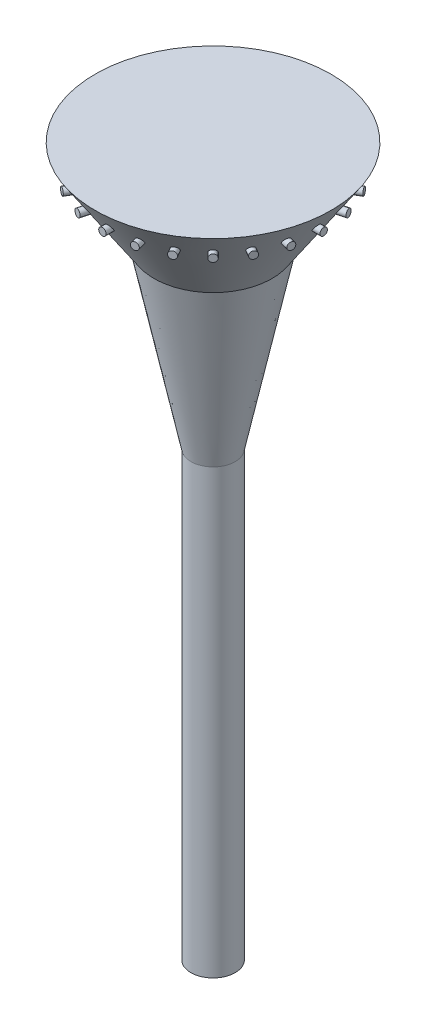
SolidWorks part; units mm, degrees
ref_plane "Front Plane" through (0, 0, 0) normal (0, 0, 1) x (1, 0, 0)
ref_plane "Top Plane" through (0, 0, 0) normal (0, 1, 0) x (1, 0, 0)
ref_plane "Right Plane" through (0, 0, 0) normal (1, 0, 0) x (0, 0, -1)
sketch "Sketch1" plane through (0, 0, 0) normal (0, 0, 1) x (1, 0, 0)
  line L6 (0, 0) -> (0, 1219.2)
  line L7 (0, 1219.2) -> (-203.2, 1219.2)
  line L8 (-38.1, 762) -> (-38.1, 0)
  line L9 (-38.1, 0) -> (0, 0)
  line L10 (-203.2, 1219.2) -> (-101.6, 1066.8)
  line L11 (-101.6, 1066.8) -> (-38.1, 762)
  point P3 (-99.6612, 1113.3987)
  dimension "D1" = 38.1
  dimension "D2" = 203.2
  dimension "D3" = 1219.2
  dimension "D4" = 762
  dimension "D5" = 152.4
  dimension "D6" = 101.6
revolve "Revolve1" add sketch "Sketch1" angle 360 about L6
sketch "Sketch2" plane through (0, 0, 0) normal (0, 0, 1) x (1, 0, 0)
  line L0 (203.2, 1219.2) -> (-203.2, 1219.2) construction
  circle A0 centre (0, 1181.1) radius 6.35
  dimension "D2" = 12.7
  dimension "D1" = 38.1
extrude "Boss-Extrude1" add sketch "Sketch2" along normal blind 190.5
pattern_circular "CirPattern1" count 24 every 15 about axis through (0, 0, 0) along (0, 1, 0) of "Boss-Extrude1"
